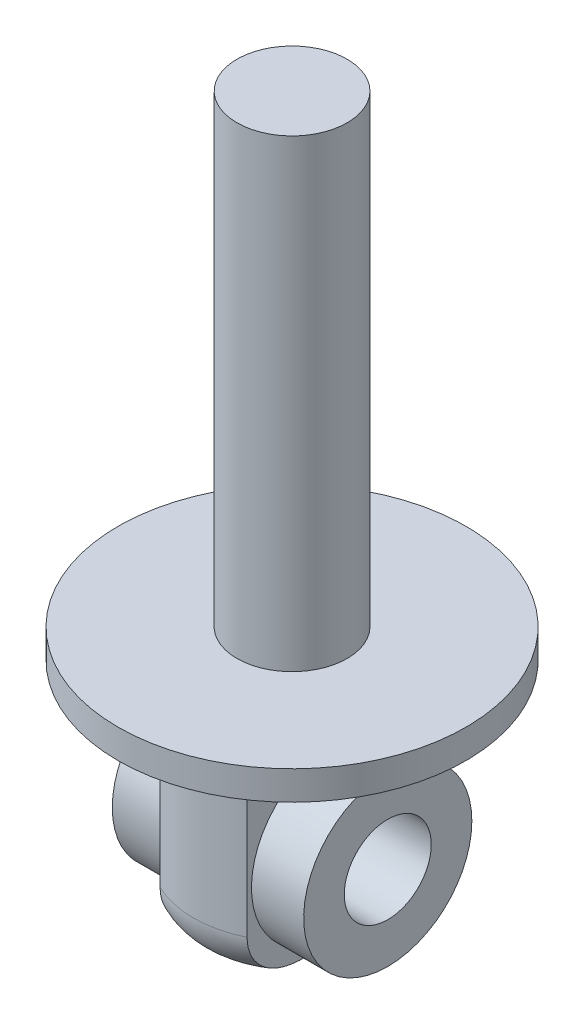
SolidWorks part; units mm, degrees
ref_plane "Front Plane" through (0, 0, 0) normal (0, 0, 1) x (1, 0, 0)
ref_plane "Top Plane" through (0, 0, 0) normal (0, 1, 0) x (1, 0, 0)
ref_plane "Right Plane" through (0, 0, 0) normal (1, 0, 0) x (0, 0, -1)
sketch "Sketch1" plane through (0, 0, 0) normal (0, 1, 0) x (1, 0, 0)
  circle A0 centre (0, 0) radius 30
  dimension "D1" = 60
extrude "Boss-Extrude1" add sketch "Sketch1" along normal blind 5
sketch "Sketch2" plane through (0, 5, 0) normal (0, 1, 0) x (1, 0, 0)
  circle A0 centre (0, 0) radius 9.5
  dimension "D1" = 19
extrude "Boss-Extrude2" add sketch "Sketch2" along normal blind 80
sketch "Sketch3" plane through (0, 0, 0) normal (0, -1, 0) x (1, 0, 0)
  circle A0 centre (0, 0) radius 17
  dimension "D1" = 34
extrude "Boss-Extrude3" add sketch "Sketch3" along normal blind 38
fillet "Fillet1" radius 8 1 edges at (0, -38, -17)
sketch "Sketch4" plane through (0, 0, 0) normal (0, 0, 1) x (1, 0, 0)
  line L0 (0, 0) -> (0, -38) construction
  line L1 (-9, -38) -> (9, -38) construction
  line L2 (-28.9186, -38) -> (28.9186, -38)
  line L3 (28.9186, -38) -> (28.9186, -8)
  line L4 (28.9186, -8) -> (7.5, -8)
  line L5 (7.5, -8) -> (7.5, -38)
  line L6 (-7.5, -8) -> (-7.5, -38)
  line L7 (-28.9186, -8) -> (-7.5, -8)
  line L8 (-28.9186, -38) -> (-28.9186, -8)
  dimension "D1" = 15
  dimension "D2" = 30
extrude "Cut-Extrude1" cut sketch "Sketch4" against normal mid plane 38 contours L8 L2 L6 L7 | L4 L5 L2 L3
sketch "Sketch8" plane through (7.5, 0, 0) normal (1, 0, 0) x (0, 0, -1)
  line L0 (0, -8) -> (0, -38) construction
  line L1 (15.2561, -8) -> (-15.2561, -8) construction
  line L2 (4.9749, -38) -> (-4.9749, -38) construction
  line L3 (-17, 0) -> (-17, -30) construction
  circle A0 centre (0, -23) radius 7.5
  dimension "D1" = 15
extrude "Cut-Extrude2" cut sketch "Sketch8" against normal through all both and the other way through all
sketch "Sketch9" plane through (0, 0, 0) normal (1, 0, 0) x (0, 0, -1)
  circle A0 centre (0, -23) radius 14.5
  circle A1 centre (0, -23) radius 7.5 construction
  circle A2 centre (0, -23) radius 7.5
  dimension "D1" = 29
extrude "Boss-Extrude4" add sketch "Sketch9" along normal mid plane 33
